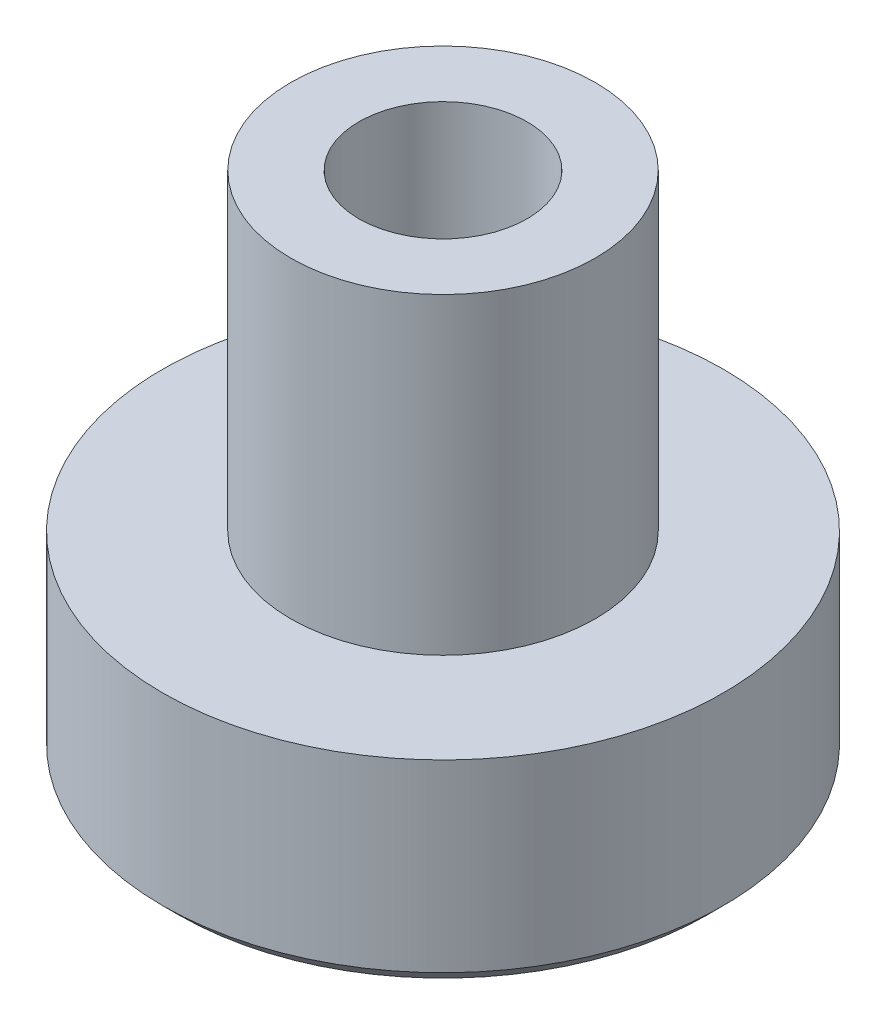
SolidWorks part; units mm, degrees
ref_plane "Front Plane" through (0, 0, 0) normal (0, 0, 1) x (1, 0, 0)
ref_plane "Top Plane" through (0, 0, 0) normal (0, 1, 0) x (1, 0, 0)
ref_plane "Right Plane" through (0, 0, 0) normal (1, 0, 0) x (0, 0, -1)
sketch "Sketch1" plane through (0, 0, 0) normal (0, 1, 0) x (1, 0, 0)
  circle A0 centre (0, 0) radius 7
  circle A1 centre (0, 0) radius 2.1
  dimension "D1" = 14
  dimension "D2" = 4.2
extrude "Boss-Extrude1" add sketch "Sketch1" along normal blind 5
ref_plane "Plane1" through (0, 5, 0) normal (0, 1, 0) x (1, 0, 0)
sketch "Sketch2" plane through (0, 5, 0) normal (0, 1, 0) x (1, 0, 0)
  circle A0 centre (0, 0) radius 3.8
  circle A1 centre (0, 0) radius 2.1
  dimension "D1" = 7.6
  dimension "D2" = 4.2
extrude "Boss-Extrude2" add sketch "Sketch2" along normal blind 7.8
chamfer "Chamfer1" distance 0.4 angle 45 1 edges at (0, 0, 7)
